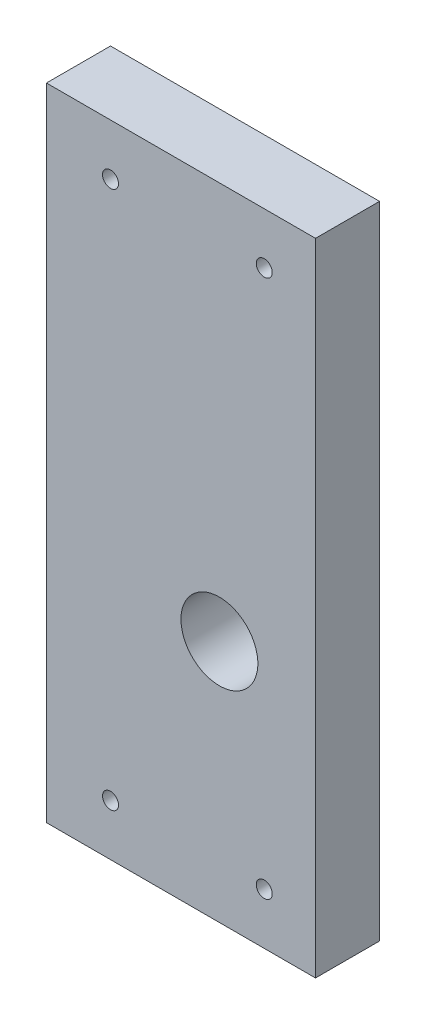
SolidWorks part; units mm, degrees
ref_plane "Front Plane" through (0, 0, 0) normal (0, 0, 1) x (1, 0, 0)
ref_plane "Top Plane" through (0, 0, 0) normal (0, 1, 0) x (1, 0, 0)
ref_plane "Right Plane" through (0, 0, 0) normal (1, 0, 0) x (0, 0, -1)
ref_plane "Plane1" through (0, 0, 10) normal (0, 0, 1) x (1, 0, 0)
sketch "Sketch1" plane through (0, 0, 10) normal (0, 0, 1) x (1, 0, 0)
  line L0 (21, 50) -> (-21, 50)
  line L1 (-21, 50) -> (-21, -50)
  line L2 (-21, -50) -> (21, -50)
  line L3 (21, -50) -> (21, 50)
extrude "Boss-Extrude1" add sketch "Sketch1" against normal blind 10
hole_wizard "Ø12.0 (12) Diameter Hole1" positions "Sketch3" profile "Sketch2" hole size "Ø12.0" standard "ANSI Metric"
sketch "Sketch3" plane through (0, 0, 0) normal (0, 0, -1) x (-1, 0, 0)
  point P0 (-6, -12)
sketch "Sketch2" plane through (6, -12, 0) normal (1, 0, 0) x (0, 1, 0)
  line L0 (0, 0) -> (0, 10)
  line L1 (0, 10) -> (6, 10)
  line L2 (6, 10) -> (6, 0)
  line L5 (6, 0) -> (0, 0)
  line L11 (0, -6.35) -> (0, 107.95) construction
  dimension "Thru Hole Dia." = 12
  dimension "Thru Hole Depth" = 10
hole_wizard "Ø2.5 (2.5) Diameter Hole1" positions "Sketch5" profile "Sketch4" hole size "Ø2.5" standard "ANSI Metric"
sketch "Sketch5" plane through (0, 0, 10) normal (0, 0, 1) x (1, 0, 0)
  point P0 (13, 42)
  point P1 (-11, 42)
  point P2 (-11, -42)
  point P3 (13, -42)
sketch "Sketch4" plane through (13, 42, 10) normal (1, 0, 0) x (0, -1, 0)
  line L0 (0, 0) -> (0, 10)
  line L1 (0, 10) -> (1.25, 10)
  line L2 (1.25, 10) -> (1.25, 0)
  line L5 (1.25, 0) -> (0, 0)
  line L11 (0, -6.35) -> (0, 107.95) construction
  dimension "Thru Hole Dia." = 2.5
  dimension "Thru Hole Depth" = 10
hole_wizard "Ø2.5 (2.5) Diameter Hole2" positions "Sketch7" profile "Sketch6" hole size "Ø2.5" standard "ANSI Metric"
sketch "Sketch7" plane through (-21, 0, 0) normal (-1, 0, 0) x (0, 0, 1)
  point P0 (5, 45)
  point P1 (5, -45)
sketch "Sketch6" plane through (-21, 45, 5) normal (0, 1, 0) x (0, 0, 1)
  line L0 (0, 0) -> (0, 8.2511)
  line L1 (0, 8.2511) -> (1.25, 7.5)
  line L2 (1.25, 7.5) -> (1.25, 0)
  line L5 (1.25, 0) -> (0, 0)
  line L10 (0, 8.2511) -> (-1.25, 7.5) construction
  line L11 (0, -6.35) -> (0, 107.95) construction
  dimension "Hole Dia." = 2.5
  dimension "Hole Depth" = 7.5
  dimension "Drill Angle" = 118
